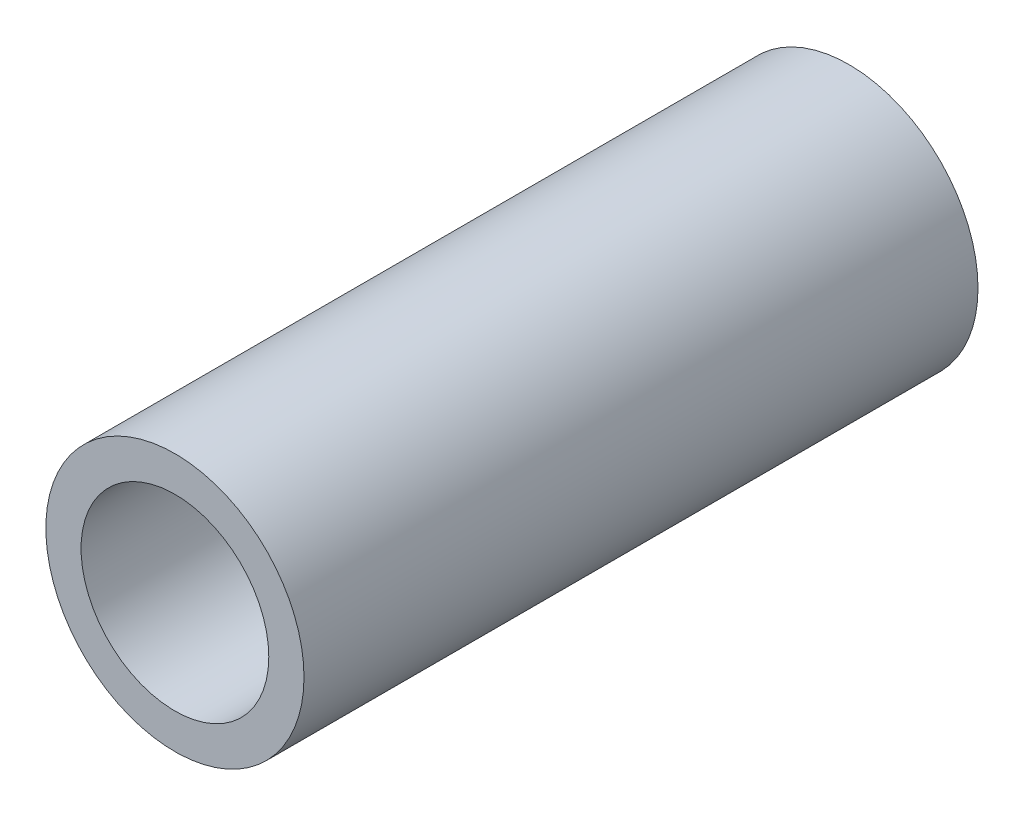
SolidWorks part; units mm, degrees
ref_plane "Front Plane" through (0, 0, 0) normal (0, 0, 1) x (1, 0, 0)
ref_plane "Top Plane" through (0, 0, 0) normal (0, 1, 0) x (1, 0, 0)
ref_plane "Right Plane" through (0, 0, 0) normal (1, 0, 0) x (0, 0, -1)
sketch "Sketch1" plane through (0, 0, 0) normal (0, 0, 1) x (1, 0, 0)
  circle A0 centre (0, 0) radius 34.925
  circle A1 centre (0, 0) radius 25.4
extrude "Boss-Extrude1" add sketch "Sketch1" along normal blind 182.372
